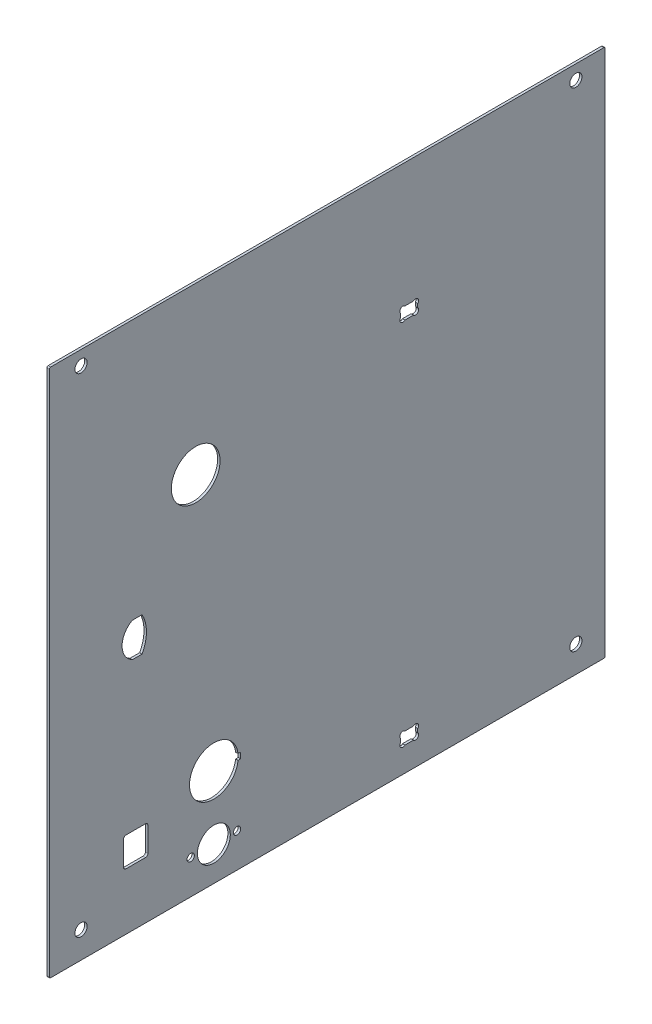
SolidWorks part; units mm, degrees
ref_plane "Front Plane" through (0, 0, 0) normal (0, 0, 1) x (1, 0, 0)
ref_plane "Top Plane" through (0, 0, 0) normal (0, 1, 0) x (1, 0, 0)
ref_plane "Right Plane" through (0, 0, 0) normal (1, 0, 0) x (0, 0, -1)
sketch "Sketch1" plane through (0, 0, 0) normal (1, 0, 0) x (0, 0, -1)
  line L0 (147.63, 88) -> (159.2524, 88) construction
  line L1 (0, 0) -> (228, 0)
  line L3 (0, 217) -> (228, 217)
  line L4 (228, 0) -> (228, 217)
  line L5 (144.13, 15) -> (151.13, 15)
  line L6 (144.13, 15) -> (144.13, 10)
  line L7 (144.13, 10) -> (151.13, 10)
  line L8 (151.13, 15) -> (151.13, 10)
  line L9 (151.13, 161) -> (151.13, 166)
  line L10 (144.13, 166) -> (151.13, 166)
  line L11 (144.13, 161) -> (144.13, 166)
  line L12 (144.13, 161) -> (151.13, 161)
  line L13 (0, 217) -> (0, 0)
  line L23 (147.63, 166) -> (147.63, 10) construction
  line L32 (77, 14) -> (58, 14) construction
  line L38 (78.5, 41.2) -> (77.4277, 41.2)
  line L39 (78.5, 41.2) -> (78.5, 38.8)
  line L40 (78.5, 38.8) -> (77.4277, 38.8)
  circle A0 centre (13, 10.85) radius 1.65 construction
  circle A1 centre (13, 10.85) radius 2.5
  circle A2 centre (13, 211.15) radius 1.65 construction
  circle A3 centre (13, 211.15) radius 2.5
  circle A4 centre (67.5, 14) radius 6.75
  circle A5 centre (216, 10.85) radius 1.65 construction
  circle A6 centre (216, 10.85) radius 2.5
  circle A7 centre (216, 211.15) radius 1.65 construction
  circle A8 centre (216, 211.15) radius 2.5
  circle A22 centre (60.05, 149) radius 10
  circle A23 centre (77, 14) radius 1.5
  circle A24 centre (58, 14) radius 1.5
  arc A25 (77.4277, 41.2) -> (57.5, 40) centre (67.5, 40) ccw
  arc A26 (57.5, 40) -> (77.4277, 38.8) centre (67.5, 40) ccw
  circle A27 centre (67.5, 40) radius 11.5 construction
  point P74 (194, 120)
  point P86 (194, 110)
  point P93 (194, 120)
  point P100 (194, 110)
  point P107 (197, 120)
  point P114 (197, 110)
  point P121 (197, 120)
  point P128 (197, 110)
  point P135 (197, 120)
  point P142 (197, 110)
  point P149 (197, 120)
  point P156 (197, 110)
  point P163 (197, 120)
  point P170 (197, 110)
  point P177 (197, 120)
  point P184 (197, 110)
  point P191 (197, 120)
  point P198 (197, 110)
  point P205 (197, 120)
  point P212 (197, 110)
  point P219 (197, 120)
  point P226 (197, 110)
  point P233 (197, 120)
  point P240 (197, 110)
  point P247 (197, 120)
  point P254 (197, 110)
  point P261 (197, 120)
  point P268 (197, 110)
  point P275 (197, 120)
  point P282 (197, 110)
  point P289 (197, 120)
  point P296 (197, 110)
  point P303 (197, 120)
  point P310 (197, 110)
  point P317 (197, 120)
  point P324 (197, 110)
  point P331 (197, 120)
  point P338 (197, 110)
  point P345 (197, 120)
  point P352 (197, 110)
  point P359 (197, 120)
  point P366 (197, 110)
  point P373 (197, 120)
  point P380 (197, 110)
  point P387 (197, 120)
  point P394 (197, 110)
  point P401 (197, 120)
  point P408 (197, 110)
  point P415 (197, 120)
  point P422 (197, 110)
  point P429 (197, 120)
  point P436 (197, 110)
  point P443 (197, 120)
  point P450 (197, 110)
  point P457 (197, 120)
  point P464 (197, 110)
  point P471 (197, 120)
  point P478 (197, 110)
  point P485 (197, 120)
  point P492 (197, 110)
  point P499 (197, 120)
  point P506 (197, 110)
  point P513 (197, 120)
  point P520 (197, 110)
  point P527 (197, 120)
  point P534 (197, 110)
  point P541 (197, 120)
  point P548 (197, 110)
  point P555 (197, 120)
  point P562 (197, 110)
  point P569 (197, 120)
  point P576 (197, 110)
  point P583 (197, 120)
  point P590 (197, 110)
  point P597 (197, 120)
  point P604 (197, 110)
  point P611 (197, 120)
  point P618 (197, 110)
  point P625 (197, 120)
  point P632 (197, 110)
  point P639 (197, 120)
  point P646 (197, 110)
  point P653 (197, 120)
  point P660 (197, 110)
  point P667 (192, 120)
  point P674 (192, 110)
  point P681 (192, 120)
  point P688 (192, 110)
  point P695 (187, 120)
  point P702 (187, 110)
  point P709 (187, 120)
  point P716 (187, 110)
  point P723 (187, 120)
  point P730 (187, 110)
  point P737 (187, 120)
  point P744 (187, 110)
  dimension "D8" = 228
  dimension "D18" = 134.63
  dimension "D26" = 156
  dimension "D27" = 20
  dimension "D17" = 3
  dimension "D32" = 13.5
  dimension "D35" = 10
  dimension "D36" = 23
  dimension "D6" = 54.5
  dimension "D24" = 3.3
  dimension "D29" = 5
  dimension "D9" = 13
  dimension "D1" = 217
  dimension "D4" = 7
  dimension "D5" = 40
  dimension "D7" = 14
  dimension "D10" = 19
  dimension "D11" = 11
  dimension "D12" = 2.4
  dimension "D13" = 10
  dimension "D14" = 203
  dimension "D15" = 200.3
  dimension "D16" = 62.15
  dimension "D19" = 47.05
  dimension "D20" = 5
  dimension "D30" = 10.85
extrude "Boss-Extrude1" add sketch "Sketch1" along normal blind 1
sketch "Sketch5" plane through (1, 0, 0) normal (1, 0, 0) x (0, 0, -1)
  line L0 (30.44, 29.265) -> (40.44, 29.265) construction
  line L1 (147.63, 166) -> (147.63, 163.5) construction
  line L2 (151.13, 166) -> (144.13, 166) construction
  line L3 (147.63, 163.5) -> (144.13, 163.5) construction
  line L4 (144.13, 166) -> (144.13, 161) construction
  line L5 (0, 0) -> (228, 0) construction
  line L6 (145.0139, 166) -> (145.0139, 165.1161) construction
  line L7 (35.38, 103.25) -> (37.05, 103.25) construction
  line L8 (29.85, 110.25) -> (29.85, 96.25) construction
  line L9 (35.44, 35.265) -> (35.44, 23.265) construction
  line L10 (30.44, 35.265) -> (40.44, 35.265) construction
  line L11 (30.44, 35.265) -> (30.44, 23.265) construction
  line L12 (30.44, 23.265) -> (40.44, 23.265) construction
  line L13 (40.44, 35.265) -> (40.44, 23.265) construction
  line L14 (35.38, 110.25) -> (37.05, 110.25) construction
  line L15 (145.0139, 165.1161) -> (144.13, 165.1161) construction
  line L16 (135.5385, 88) -> (160.2022, 88) construction
  line L17 (144.13, 161) -> (151.13, 161) construction
  line L21 (35.38, 110.25) -> (35.38, 96.25) construction
  line L22 (35.38, 96.25) -> (37.05, 96.25) construction
  line L23 (37.05, 110.25) -> (37.05, 96.25) construction
  line L24 (34.05, 110.25) -> (38.05, 110.25)
  line L25 (39.85, 96.25) -> (39.85, 110.25) construction
  line L26 (34.05, 96.25) -> (38.05, 96.25)
  line L27 (38.05, 110.25) -> (38.05, 96.25) construction
  line L28 (38.05, 103.25) -> (35.38, 103.25) construction
  line L29 (151.13, 15) -> (144.13, 15) construction
  line L31 (31.44, 35.265) -> (39.44, 35.265)
  line L32 (30.44, 34.265) -> (30.44, 24.265)
  line L33 (31.44, 23.265) -> (39.44, 23.265)
  line L34 (40.44, 34.265) -> (40.44, 24.265)
  circle A0 centre (145.0139, 165.1161) radius 1.25
  circle A1 centre (150.2461, 165.1161) radius 1.25
  arc A2 (30.44, 24.265) -> (31.44, 23.265) centre (31.44, 24.265) ccw
  arc A3 (39.44, 23.265) -> (40.44, 24.265) centre (39.44, 24.265) ccw
  circle A4 centre (13, 10.85) radius 1.65 construction
  arc A5 (39.44, 35.265) -> (40.44, 34.265) centre (39.44, 34.265) cw
  arc A6 (34.05, 96.25) -> (34.05, 110.25) centre (37.7833, 103.25) cw
  arc A7 (38.05, 110.25) -> (38.05, 96.25) centre (25.3389, 103.25) cw
  circle A8 centre (145.0139, 161.8839) radius 1.25
  circle A9 centre (150.2461, 161.8839) radius 1.25
  circle A10 centre (150.2461, 14.1161) radius 1.25
  circle A11 centre (150.2461, 10.8839) radius 1.25
  circle A12 centre (145.0139, 10.8839) radius 1.25
  circle A13 centre (145.0139, 14.1161) radius 1.25
  arc A14 (31.44, 35.265) -> (30.44, 34.265) centre (31.44, 34.265) ccw
  dimension "D10" = 3.3
  dimension "D8" = 1
  dimension "D4" = 2.5
  dimension "D2" = 24.05
  dimension "D3" = 22.44
  dimension "D5" = 29.265
  dimension "D6" = 10
  dimension "D7" = 12
  dimension "D12" = 1.67
  dimension "D13" = 14
  dimension "D14" = 1
  dimension "D15" = 4
  dimension "D16" = 8.2
  dimension "D17" = 10
  dimension "D18" = 92.4
extrude "Cut-Extrude3" cut sketch "Sketch5" against normal through all
fillet "Fillet1" radius 0.5 4 edges at (0.5, 217, 0) (0.5, 217, -228) (0.5, 0, -228) (0.5, 0, 0)
